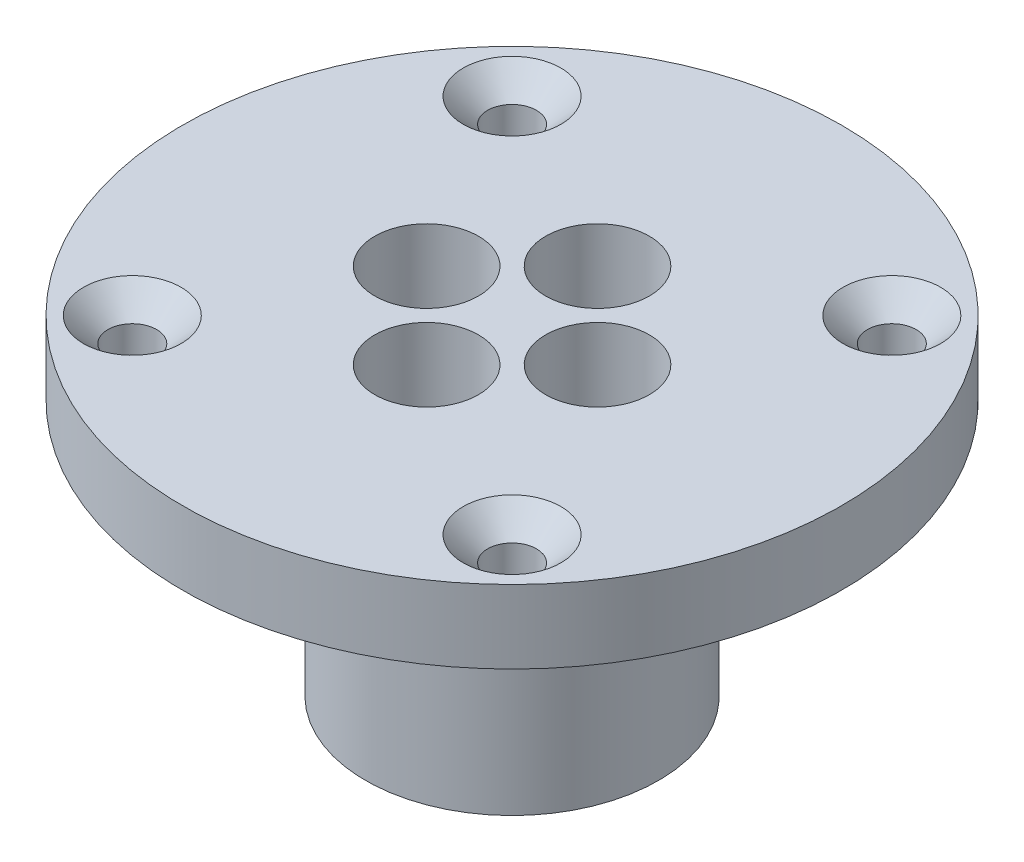
SolidWorks part; units mm, degrees
ref_plane "Plano frontal" through (0, 0, 0) normal (0, 0, 1) x (1, 0, 0)
ref_plane "Plano superior" through (0, 0, 0) normal (0, 1, 0) x (1, 0, 0)
ref_plane "Plano direito" through (0, 0, 0) normal (1, 0, 0) x (0, 0, -1)
sketch "Esboço1" plane through (0, 0, 0) normal (0, 0, 1) x (1, 0, 0)
  line L0 (0, 0) -> (0, 25)
  line L1 (0, 25) -> (27, 25)
  line L2 (27, 25) -> (27, 19)
  line L3 (27, 19) -> (12, 19)
  line L4 (12, 19) -> (12, 0)
  line L5 (12, 0) -> (0, 0)
  dimension "D1" = 27
  dimension "D2" = 12
  dimension "D3" = 19
  dimension "D4" = 6
revolve "Revolução1" add sketch "Esboço1" angle 360 about L0
sketch "Esboço2" plane through (0, 0, 0) normal (0, -1, 0) x (1, 0, 0)
  line L0 (0, 0) -> (0, 7) construction
  circle A0 centre (0, 7) radius 1.75
  dimension "D2" = 3.5
  dimension "D1" = 7
extrude "Corte-extrusão1" cut sketch "Esboço2" against normal blind 6
sketch "Esboço3" plane through (0, 6, 0) normal (0, -1, 0) x (1, 0, 0)
  circle A0 centre (0, 7) radius 4.25
  dimension "D1" = 8.5
extrude "Corte-extrusão2" cut sketch "Esboço3" against normal through all
pattern_circular "PadrãoCircular1" count 4 over 360 about axis through (0, 0, 0) along (0, 1, 0) of "Corte-extrusão2", "Corte-extrusão1"
chamfer "Chanfro1" distance 2 angle 45 4 edges at (0, 6, -5.25) (-5.25, 6, 0) (0, 6, 5.25) (5.25, 6, 0)
sketch "Esboço4" plane through (0, 25, 0) normal (0, 1, 0) x (1, 0, 0)
  line L0 (0, 0) -> (0, 27) construction
  line L1 (0, 0) -> (-15.5563, 15.5563) construction
  circle A0 centre (0, 0) radius 27 construction
  circle A1 centre (-15.5563, 15.5563) radius 2
  dimension "D2" = 4
  dimension "D1" = 22
  dimension "D3" = 45
extrude "Corte-extrusão3" cut sketch "Esboço4" against normal through all
pattern_circular "PadrãoCircular2" count 4 over 360 about axis through (0, 0, 0) along (0, 1, 0) of "Corte-extrusão3"
chamfer "Chanfro3" distance 2 angle 45 4 edges at (13.5563, 25, -15.5563) (-15.5563, 25, -13.5563) (-13.5563, 25, 15.5563) (15.5563, 25, 13.5563)
sketch "Esboço5" plane through (0, 0, 0) normal (0, -1, 0) x (1, 0, 0)
  circle A0 centre (-7, 0) radius 1.75 construction
  circle A1 centre (0, 0) radius 12
  circle A2 centre (0, 0) radius 12
  circle A3 centre (0, -7) radius 1.75 construction
  circle A4 centre (7, 0) radius 1.75 construction
  circle A5 centre (0, 7) radius 1.75 construction
  circle A6 centre (-7, 0) radius 1.75
  circle A7 centre (0, -7) radius 1.75
  circle A8 centre (7, 0) radius 1.75
  circle A9 centre (0, 7) radius 1.75
  dimension "D1" = 0
extrude "Ressalto-extrusão2" add sketch "Esboço5" along normal blind 2
